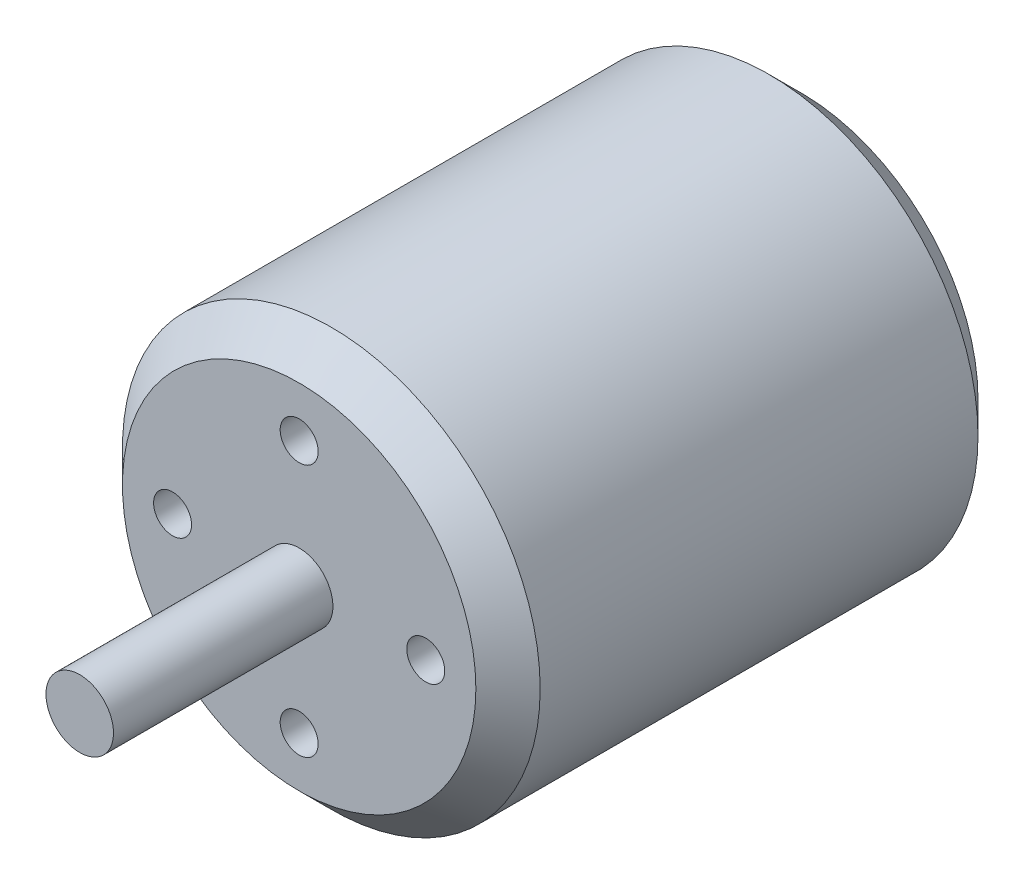
SolidWorks part; units mm, degrees
ref_plane "Front Plane" through (0, 0, 0) normal (0, 0, 1) x (1, 0, 0)
ref_plane "Top Plane" through (0, 0, 0) normal (0, 1, 0) x (1, 0, 0)
ref_plane "Right Plane" through (0, 0, 0) normal (1, 0, 0) x (0, 0, -1)
sketch "Sketch1" plane through (0, 0, 0) normal (0, 0, 1) x (1, 0, 0)
  circle A0 centre (0, 0) radius 24.75
extrude "Boss-Extrude1" add sketch "Sketch1" along normal blind 59.5
sketch "Sketch2" plane through (0, 0, 59.5) normal (0, 0, 1) x (1, 0, 0)
  circle A0 centre (0, 0) radius 4
extrude "Boss-Extrude2" add sketch "Sketch2" along normal blind 26
chamfer "Chamfer1" distance 3.81 angle 45 1 edges at (24.75, 0, 59.5)
chamfer "Chamfer2" distance 3.81 angle 45 1 edges at (24.75, 0, 0)
sketch "Sketch3" plane through (0, 0, 59.5) normal (0, 0, 1) x (1, 0, 0)
  circle A0 centre (0, 0) radius 15 construction
  circle A1 centre (0, 15) radius 2.25
  circle A2 centre (15, 0) radius 2.25
  circle A3 centre (0, -15) radius 2.25
  circle A4 centre (-15, 0) radius 2.25
  point P3 (-15, 0)
  point P4 (0, 15)
  point P5 (15, 0)
  point P6 (0, -15)
  point P7 (15, 0)
  point P8 (-15, 0)
  point P9 (0, 15)
  dimension "D1" = 4
extrude "Cut-Extrude3" cut sketch "Sketch3" against normal blind 12.7
sketch "Sketch4" plane through (0, 0, 0) normal (0, 0, -1) x (-1, 0, 0)
  circle A0 centre (0, 0) radius 4
extrude "Boss-Extrude3" [suppressed] add sketch "Sketch4" along normal blind 19.05
